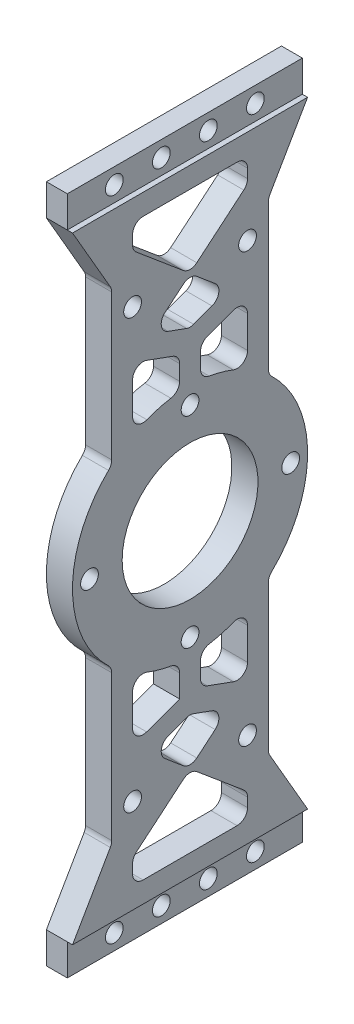
SolidWorks part; units mm, degrees
material "Сплав 2024"
ref_plane "Спереди" through (0, 0, 0) normal (0, 0, 1) x (1, 0, 0)
ref_plane "Сверху" through (0, 0, 0) normal (0, 1, 0) x (1, 0, 0)
ref_plane "Справа" through (0, 0, 0) normal (1, 0, 0) x (0, 0, -1)
sketch "Эскиз1" plane through (0, 0, 0) normal (0, 1, 0) x (1, 0, 0)
  line L1 (0, 0) -> (5, 0)
  line L2 (0, 0) -> (0, -30)
  line L3 (0, -30) -> (5, -30)
  line L4 (5, 0) -> (5, -30)
  dimension "D1" = 5
  dimension "D2" = 30
extrude "Бобышка-Вытянуть1" add sketch "Эскиз1" along normal blind 130
sketch "Эскиз2" plane through (0, 0, 0) normal (-1, 0, 0) x (0, 0, 1)
  line L0 (30, 65) -> (0, 65) construction
  line L1 (30, 130) -> (30, 0) construction
  line L2 (0, 130) -> (0, 0) construction
  line L3 (15, 130) -> (15, 0) construction
  line L4 (0, 130) -> (30, 130) construction
  line L5 (0, 0) -> (30, 0) construction
  circle A0 centre (15, 65) radius 22.5
  dimension "D1" = 45
extrude "Бобышка-Вытянуть2" add sketch "Эскиз2" against normal up to surface (5 mm away) up to face at (5, 65, 15)
sketch "Эскиз3" plane through (0, 0, 0) normal (-1, 0, 0) x (0, 0, 1)
  circle A0 centre (15, 65) radius 13
  dimension "D1" = 26
extrude "Вырез-Вытянуть1" cut sketch "Эскиз3" against normal through all
sketch "Эскиз4" plane through (5, 0, 0) normal (-1, 0, 0) x (0, 0, 1)
  line L0 (15, 87.5) -> (15, 42.5) construction
  line L1 (15, 130) -> (15, 0) construction
  line L2 (37.5, 65) -> (-7.5, 65) construction
  circle A0 centre (15, 65) radius 19.25 construction
  circle A1 centre (15, 65) radius 22.5 construction
  dimension "D1" = 38.5
hole_wizard "Отверстие с зазором M33" positions "Эскиз6" profile "Эскиз5" hole size "M3" standard "Ansi Metric" end condition through all
sketch "Эскиз6" plane through (5, -25.0247, 7.2629) normal (-1, 0, 0) x (0, 0, 1)
  line L0 (7.7371, 112.5247) -> (7.7371, 67.5247) construction
  line L1 (30.2371, 90.0247) -> (-14.7629, 90.0247) construction
  circle A0 centre (7.7371, 90.0247) radius 19.25 construction
  point P0 (7.7371, 109.2747)
  point P6 (-11.5129, 90.0247)
  point P10 (7.7371, 70.7747)
  point P12 (26.9871, 90.0247)
sketch "Эскиз5" plane through (5, 84.25, 15) normal (0, 1, 0) x (0, 0, -1)
  line L0 (0, 0) -> (0, 5)
  line L1 (0, 5) -> (1.7, 5)
  line L2 (1.7, 5) -> (1.7, 0)
  line L5 (1.7, 0) -> (0, 0)
  line L11 (0, -6.35) -> (0, 107.95) construction
  dimension "Диаметр сквозного отверстия" = 3.4
  dimension "Глубина сквозного отверстия" = 5
sketch "Эскиз8" plane through (5, 0, 0) normal (1, 0, 0) x (0, 0, -1)
  line L0 (-15, 130) -> (-15, 0) construction
  line L1 (-30, 130) -> (0, 130) construction
  line L2 (-30, 0) -> (0, 0) construction
  line L3 (19.447, 65) -> (-49.447, 65) construction
  line L4 (0, 130) -> (0, 81.7705) construction
  line L5 (-26, 106) -> (-4, 106) construction
  line L6 (-26, 106) -> (-26, 24) construction
  line L7 (-26, 24) -> (-4, 24) construction
  line L8 (-4, 106) -> (-4, 24) construction
  line L9 (-26, 106) -> (-4, 24) construction
  line L10 (-26, 24) -> (-4, 106) construction
  point P8 (-15, 65)
  point P9 (-15, 65)
  dimension "D1" = 4
  dimension "D2" = 82
hole_wizard "Отверстие с зазором M32" positions "Эскиз10" profile "Эскиз9" hole size "M3" standard "Ansi Metric" end condition through all
sketch "Эскиз10" plane through (5, 0, 0) normal (1, 0, 0) x (0, 0, -1)
  point P0 (-26, 106)
  point P3 (-4, 106)
  point P6 (-4, 24)
  point P9 (-26, 24)
sketch "Эскиз9" plane through (5, 106, 26) normal (0, 1, 0) x (0, 0, -1)
  line L0 (0, 0) -> (0, 5)
  line L1 (0, 5) -> (1.7, 5)
  line L2 (1.7, 5) -> (1.7, 0)
  line L5 (1.7, 0) -> (0, 0)
  line L11 (0, -6.35) -> (0, 107.95) construction
  dimension "Диаметр сквозного отверстия" = 3.4
  dimension "Глубина сквозного отверстия" = 5
sketch "Эскиз11" plane through (5, 0, 0) normal (1, 0, 0) x (0, 0, -1)
  line L0 (-15, 130) -> (-15, 0) construction
  line L1 (-30, 130) -> (0, 130) construction
  line L2 (-30, 0) -> (0, 0) construction
  line L3 (-37.5, 124) -> (-30, 111.0096)
  line L4 (-37.5, 124) -> (7.5, 124) construction
  line L5 (-37.5, 124) -> (-37.5, 130)
  line L6 (-37.5, 130) -> (7.5, 130)
  line L7 (7.5, 124) -> (7.5, 130)
  line L8 (-37.5, 124) -> (7.5, 130) construction
  line L9 (-37.5, 130) -> (7.5, 124) construction
  line L10 (-30, 130) -> (-30, 81.7705) construction
  line L11 (-30, 111.0096) -> (0, 111.0096)
  line L12 (0, 130) -> (0, 81.7705) construction
  line L13 (0, 111.0096) -> (7.5, 124)
  line L14 (-37.5, 127) -> (7.5, 127) construction
  line L15 (-28.5, 130) -> (-28.5, 124) construction
  line L16 (-19.5, 130) -> (-19.5, 124) construction
  line L17 (-10.5, 130) -> (-10.5, 124) construction
  line L18 (-1.5, 130) -> (-1.5, 124) construction
  line L19 (-15, 65) -> (-5.455, 65) construction
  line L20 (-1.5, 0) -> (-1.5, 6) construction
  line L21 (-10.5, 0) -> (-10.5, 6) construction
  line L22 (-19.5, 0) -> (-19.5, 6) construction
  line L23 (-28.5, 0) -> (-28.5, 6) construction
  line L24 (-37.5, 3) -> (7.5, 3) construction
  line L25 (-37.5, 0) -> (7.5, 6) construction
  line L26 (-37.5, 6) -> (7.5, 0) construction
  line L27 (-37.5, 6) -> (7.5, 6) construction
  line L28 (0, 18.9904) -> (7.5, 6)
  line L29 (-30, 18.9904) -> (0, 18.9904)
  line L30 (7.5, 6) -> (7.5, 0)
  line L31 (-37.5, 0) -> (7.5, 0)
  line L32 (-37.5, 6) -> (-37.5, 0)
  line L33 (-37.5, 6) -> (-30, 18.9904)
  point P6 (-15, 127)
  point P45 (-15, 3)
  dimension "D1" = 6
  dimension "D2" = 45
  dimension "D3" = 120
  dimension "D4" = 9
  dimension "D5" = 9
  dimension "D6" = 9
  dimension "D7" = 9
extrude "Бобышка-Вытянуть3" add sketch "Эскиз11" against normal up to surface (5 mm away) up to face at (0, 106, 24.3)
hole_wizard "Отверстие с зазором M31" positions "Эскиз13" profile "Эскиз12" hole size "M3" standard "Ansi Metric" end condition through all
sketch "Эскиз13" plane through (5, 0, 0) normal (1, 0, 0) x (0, 0, -1)
  line L0 (-28.5, 130) -> (-28.5, 124) construction
  line L1 (-19.5, 130) -> (-19.5, 124) construction
  line L2 (-10.5, 130) -> (-10.5, 124) construction
  line L3 (-1.5, 130) -> (-1.5, 124) construction
  line L4 (-28.5, 0) -> (-28.5, 6) construction
  line L5 (-19.5, 0) -> (-19.5, 6) construction
  line L6 (-10.5, 0) -> (-10.5, 6) construction
  line L7 (-1.5, 0) -> (-1.5, 6) construction
  point P0 (-28.5, 127)
  point P4 (-19.5, 127)
  point P8 (-10.5, 127)
  point P12 (-1.5, 127)
  point P16 (-28.5, 3)
  point P20 (-19.5, 3)
  point P24 (-10.5, 3)
  point P28 (-1.5, 3)
sketch "Эскиз12" plane through (5, 127, 28.5) normal (0, 1, 0) x (0, 0, -1)
  line L0 (0, 0) -> (0, 5)
  line L1 (0, 5) -> (1.7, 5)
  line L2 (1.7, 5) -> (1.7, 0)
  line L5 (1.7, 0) -> (0, 0)
  line L11 (0, -6.35) -> (0, 107.95) construction
  dimension "Диаметр сквозного отверстия" = 3.4
  dimension "Глубина сквозного отверстия" = 5
sketch "Эскиз14" plane through (5, 0, 0) normal (1, 0, 0) x (0, 0, -1)
  line L1 (-37.5, 130) -> (7.5, 130)
  line L2 (-37.5, 130) -> (-37.5, 124)
  line L3 (-37.5, 124) -> (7.5, 124)
  line L4 (7.5, 130) -> (7.5, 124)
  line L5 (-37.5, 0) -> (7.5, 0)
  line L6 (-37.5, 0) -> (-37.5, 6)
  line L7 (-37.5, 6) -> (7.5, 6)
  line L8 (7.5, 0) -> (7.5, 6)
extrude "Вырез-Вытянуть2" cut sketch "Эскиз14" against normal blind 1
sketch "Эскиз15" plane through (5, 0, 0) normal (1, 0, 0) x (0, 0, -1)
  line L0 (-26, 0) -> (-26, 130) construction
  line L1 (-37.5, 0) -> (7.5, 0) construction
  line L2 (7.5, 130) -> (-37.5, 130) construction
  line L3 (-4, 130) -> (-4, 0) construction
  line L4 (-30, 48.2295) -> (-30, 18.9904) construction
  line L5 (0, 48.2295) -> (0, 18.9904) construction
  line L6 (-15, 65) -> (0, 65) construction
  line L7 (-17, 42.5891) -> (-17, 36.5058)
  line L8 (-13, 42.5891) -> (-13, 36.5058)
  line L9 (-15, 130) -> (-15, 0) construction
  line L10 (-26, 24) -> (-4, 24) construction
  line L11 (-17, 36.5058) -> (-26, 33.2301)
  line L12 (-26, 33.2301) -> (-26, 45.3722)
  line L13 (-13, 36.5058) -> (-4, 33.2301)
  line L14 (-4, 33.2301) -> (-4, 45.3722)
  line L15 (-15, 32.9771) -> (-22.4618, 30.2612)
  line L16 (-22.4618, 30.2612) -> (-15, 24)
  line L17 (-15, 24) -> (-7.5382, 30.2612)
  line L18 (-7.5382, 30.2612) -> (-15, 32.9771)
  line L19 (-26, 33.2301) -> (-15, 24) construction
  line L20 (-4, 33.2301) -> (-15, 24) construction
  line L21 (-30, 23.9) -> (0, 23.9) construction
  line L22 (-15, 23.9) -> (-26, 14.6699) construction
  line L23 (-15, 23.9) -> (-4, 14.6699) construction
  line L24 (-4, 14.6699) -> (-26, 14.6699) construction
  line L25 (-15, 23.9) -> (-26, 14.6699)
  line L26 (-35.1906, 10) -> (5.1906, 10) construction
  line L27 (-30, 18.9904) -> (-37.5, 6) construction
  line L28 (7.5, 6) -> (0, 18.9904) construction
  line L29 (7.5, 6) -> (-37.5, 6) construction
  line L30 (-26, 14.6699) -> (-26, 10)
  line L31 (-26, 10) -> (-4, 10)
  line L32 (-4, 10) -> (-4, 14.6699)
  line L33 (-4, 14.6699) -> (-15, 23.9)
  line L34 (-13, 87.4109) -> (-13, 93.4942)
  line L35 (-13, 93.4942) -> (-4, 96.7699)
  line L36 (-4, 96.7699) -> (-4, 84.6278)
  line L37 (-26, 96.7699) -> (-26, 84.6278)
  line L38 (-17, 93.4942) -> (-26, 96.7699)
  line L39 (-17, 87.4109) -> (-17, 93.4942)
  line L40 (-7.5382, 99.7388) -> (-15, 97.0229)
  line L41 (-15, 97.0229) -> (-22.4618, 99.7388)
  line L42 (-22.4618, 99.7388) -> (-15, 106)
  line L43 (-15, 106) -> (-7.5382, 99.7388)
  line L44 (-4, 120) -> (-4, 115.3301)
  line L45 (-4, 115.3301) -> (-15, 106.1)
  line L46 (-15, 106.1) -> (-26, 115.3301)
  line L47 (-26, 115.3301) -> (-26, 120)
  line L48 (-26, 120) -> (-4, 120)
  circle A0 centre (-15, 65) radius 22.5 construction
  arc A1 (-26, 45.3722) -> (-17, 42.5891) centre (-15, 65) ccw
  arc A2 (-13, 42.5891) -> (-4, 45.3722) centre (-15, 65) ccw
  arc A3 (-13, 87.4109) -> (-4, 84.6278) centre (-15, 65) cw
  arc A4 (-26, 84.6278) -> (-17, 87.4109) centre (-15, 65) cw
  point P22 (-26, 45.3722)
  point P23 (-4, 45.3722)
  point P40 (-15, 23.9)
  dimension "D5" = 110
  dimension "D1" = 4
  dimension "D2" = 4
  dimension "D3" = 4
  dimension "D4" = 2
  dimension "D6" = 100
  dimension "D7" = 4
  dimension "D8" = 0.1
  dimension "D9" = 4
  dimension "D10" = 100
extrude "Вырез-Вытянуть3" cut sketch "Эскиз15" against normal up to next
fillet "Скругление1" radius 2 8 edges at (2.5, 111.0096, 0) (2.5, 81.7705, 0) (2.5, 48.2295, 0) (2.5, 18.9904, 0) (2.5, 18.9904, 30) (2.5, 48.2295, 30) (2.5, 81.7705, 30) (2.5, 111.0096, 30)
fillet "Скругление2" radius 2 33 edges at (2.5, 14.6699, 4) (2.5, 10, 4) (2.5, 14.6699, 26) (2.5, 10, 26) (2.5, 24, 15) (2.5, 33.2301, 4) (2.5, 30.2612, 7.5382) (2.5, 30.2612, 22.4618) (2.5, 36.5058, 13) (2.5, 33.2301, 26) (2.5, 45.3722, 4) (2.5, 42.5891, 17) (2.5, 23.9, 15) (2.5, 32.9771, 15) (2.5, 45.3722, 26) (2.5, 42.5891, 13) (2.5, 84.6278, 26) (2.5, 96.7699, 26) (2.5, 87.4109, 13) (2.5, 93.4942, 13) (2.5, 84.6278, 4) (2.5, 96.7699, 4) (2.5, 93.4942, 17) (2.5, 87.4109, 17) (2.5, 99.7388, 7.5382) (2.5, 97.0229, 15) (2.5, 99.7388, 22.4618) (2.5, 106, 15) (2.5, 120, 4) (2.5, 115.3301, 4) (2.5, 106.1, 15) (2.5, 115.3301, 26) (2.5, 120, 26)
equation "\"D4@Эскиз11\"=\"D2@Эскиз11\"/5"
equation "\"D5@Эскиз11\"=\"D4@Эскиз11\""
equation "\"D6@Эскиз11\"=\"D4@Эскиз11\""
equation "\"D7@Эскиз11\"=\"D4@Эскиз11\""
